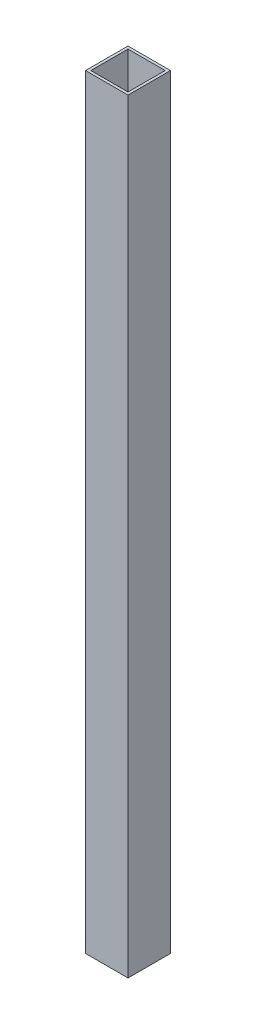
SolidWorks part; units mm, degrees
material "6061 Alloy"
ref_plane "Front Plane" through (0, 0, 0) normal (0, 0, 1) x (1, 0, 0)
ref_plane "Top Plane" through (0, 0, 0) normal (0, 1, 0) x (1, 0, 0)
ref_plane "Right Plane" through (0, 0, 0) normal (1, 0, 0) x (0, 0, -1)
sketch "Sketch1" plane through (0, 0, 0) normal (0, 1, 0) x (1, 0, 0)
  line L1 (-12.7, -12.7) -> (12.7, -12.7)
  line L2 (-12.7, -12.7) -> (-12.7, 12.7)
  line L3 (-12.7, 12.7) -> (12.7, 12.7)
  line L4 (12.7, -12.7) -> (12.7, 12.7)
  line L7 (-11.1125, -11.1125) -> (11.1125, -11.1125)
  line L8 (-11.1125, -11.1125) -> (-11.1125, 11.1125)
  line L9 (-11.1125, 11.1125) -> (11.1125, 11.1125)
  line L10 (11.1125, -11.1125) -> (11.1125, 11.1125)
  point P6 (0, 0)
  dimension "D1" = 25.4
  dimension "D2" = 25.4
  dimension "D3" = 1.5875
  dimension "D4" = 1.5875
  dimension "D5" = 1.5875
extrude "Boss-Extrude1" add sketch "Sketch1" along normal blind 457.2
